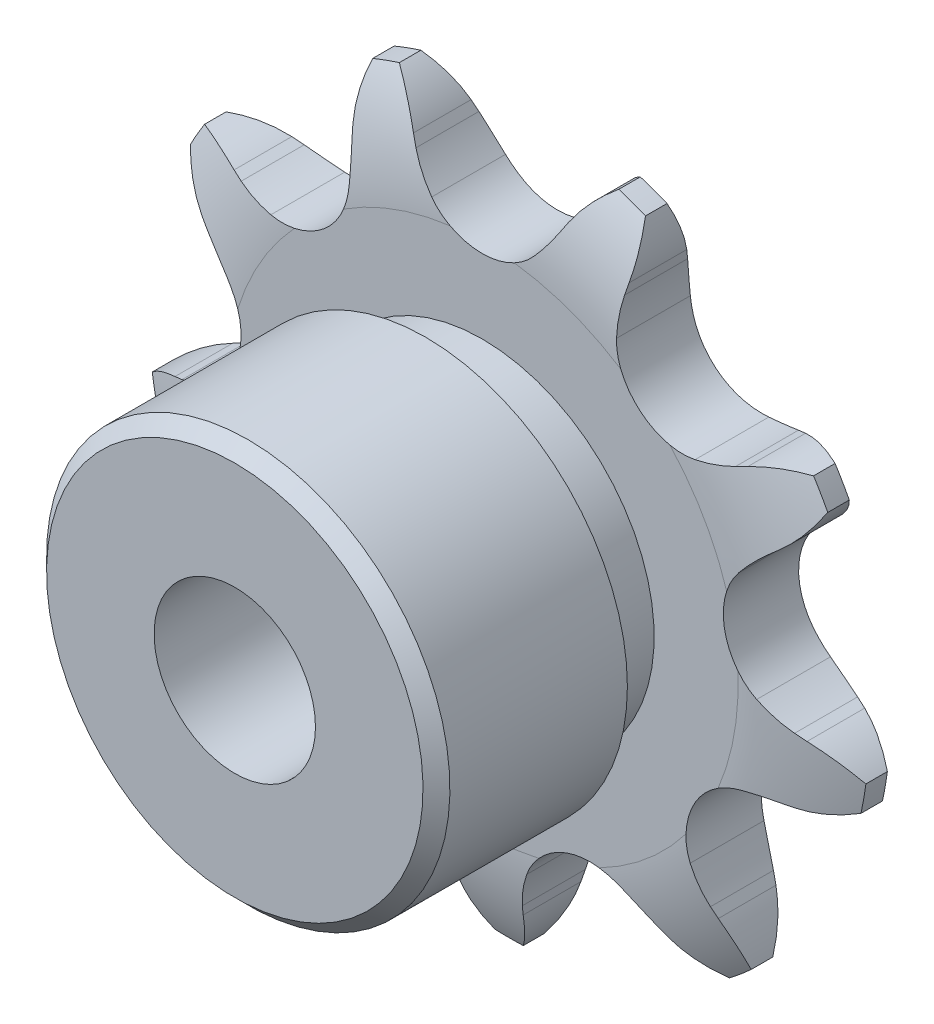
SolidWorks part; units mm, degrees
ref_plane "Front Plane" through (0, 0, 0) normal (0, 0, 1) x (1, 0, 0)
ref_plane "Top Plane" through (0, 0, 0) normal (0, 1, 0) x (1, 0, 0)
ref_plane "Right Plane" through (0, 0, 0) normal (1, 0, 0) x (0, 0, -1)
sketch "Sketch0" plane through (0, 0, 0) normal (0, 0, 1) x (1, 0, 0)
  line L0 (4, -10.9899) -> (0, 0) construction
  line L1 (0, 0) -> (10.1284, -5.8476) construction
  line L2 (0, 0) -> (-4, -10.9899) construction
  line L3 (4, -10.9899) -> (10.1284, -5.8476) construction
  line L4 (4, -10.9899) -> (-4, -10.9899) construction
  line L5 (6.6169, -9.7493) -> (6.322, -9.5008)
  line L6 (4, -10.9899) -> (0, -12.4458) construction
  line L7 (1.1979, -11.7217) -> (1.2641, -11.3417)
  line L8 (0, -10.9899) -> (0, -13.3899) construction
  line L9 (5.2105, -8.7449) -> (2.1016, -14.5107) construction
  line L10 (0, 0) -> (0, -10.9899) construction
  line L11 (6.322, -9.5008) -> (2.1016, -14.5107) construction
  line L12 (0, -13.3899) -> (0, -14.0161) construction
  line L13 (9.3623, -6.4904) -> (6.6169, -9.7493) construction
  circle A0 centre (0, 0) radius 13.3899 construction
  circle A1 centre (0, 0) radius 11.6952 construction
  arc A2 (-4.1222, -15.1007) -> (12.8643, -8.9181) centre (0, 0) ccw
  circle A3 centre (0, 0) radius 14.0161 construction
  circle A4 centre (4, -10.9899) radius 2.5 construction
  arc A7 (5.2105, -8.7449) -> (1.6296, -10.0482) centre (4, -10.9899) ccw
  circle A8 centre (4, -10.9899) radius 2.5506 construction
  arc A9 (6.6169, -9.7493) -> (12.8643, -8.9181) centre (9.3623, -6.4904) ccw
  arc A10 (6.322, -9.5008) -> (5.2105, -8.7449) centre (2.1016, -14.5107) ccw
  arc A11 (1.1979, -11.7217) -> (-4.1222, -15.1007) centre (-3, -10.9899) cw
  arc A12 (1.2641, -11.3417) -> (1.6296, -10.0482) centre (7.7174, -12.4667) cw
  dimension "D1" = 2.5506
  dimension "Dr" = 5
  dimension "Ds" = 5.1012
  dimension "R" = 2.5506
  dimension "Pitch" = 8
  dimension "A" = 41.667
  dimension "360/N" = 40
  dimension "B" = 11.778
  dimension "ab" = 7
  dimension "J" = 2.4
  dimension "ac" = 4
sketch "Sketch1" plane through (0, 0, 0) normal (1, 0, 0) x (0, 0, -1)
  line L0 (1.4, 0) -> (-1.4, 0)
  line L1 (-1.4, 0) -> (-1.4, 9.5169)
  line L2 (-1.4, 11.6952) -> (0, 11.6952) construction
  line L3 (-0.4, 13.3899) -> (0.4, 13.3899)
  line L5 (1.4, 9.5169) -> (1.4, 0)
  line L7 (0, 13.3899) -> (0, 0) construction
  line L8 (-1.4, 9.5169) -> (1.4, 9.5169) construction
  line L9 (0, 13.3899) -> (0, -13.3899) construction
  line L10 (-1.4, 9.5169) -> (-1.4, 13.3899) construction
  line L11 (-1.4, 13.3899) -> (-0.4, 13.3899) construction
  line L12 (0.4, 13.3899) -> (1.4, 13.3899) construction
  line L13 (1.4, 13.3899) -> (1.4, 9.5169) construction
  line L14 (0, 0) -> (-6.4008, 0) construction
  line L15 (-1.4, 11.6952) -> (-1.4, 6.3952) construction
  line L22 (1.4, 0) -> (-10.6, 0) construction
  line L24 (-1.4, 0) -> (-1.4, 6.3952) construction
  arc A0 (-0.4, 13.3899) -> (-1.4, 9.5169) centre (6.6, 9.5169) ccw
  arc A1 (0.4, 13.3899) -> (1.4, 9.5169) centre (-6.6, 9.5169) cw
  dimension "R" = 8
  dimension "t" = 2.8
  dimension "C" = 1
  dimension "A" = 3.873
  dimension "K" = 6.4008
  dimension "Width" = 12
  dimension "H" = 5.3
revolve "Revolve1" add sketch "Sketch1" angle 360 about L0
extrude "Cut-Extrude1" cut sketch "Sketch0" against normal through all and the other way through all
pattern_circular "CirPattern1" count 9 over 360 about axis through (0, 0, 0) along (0, 0, 1) of "Cut-Extrude1"
sketch "Sketch2" plane through (0, 0, 0) normal (0, 0, 1) x (1, 0, 0)
  circle A0 centre (0, 0) radius 3 construction
  circle A1 centre (0, 0) radius 7.5
  circle A2 centre (0, 0) radius 13.39 construction
  dimension "Bore" = 6
  dimension "Hub Dia." = 15
  dimension "OD" = 26.78
extrude "Boss-Extrude1" add sketch "Sketch2" along normal up to vertex (10.6 mm away) from surface at 1.4 starting at face at (0, 0, 1.4)
sketch "Sketch3" plane through (0, 0, 0) normal (0, 0, 1) x (1, 0, 0)
  circle A0 centre (0, 0) radius 3 construction
  circle A1 centre (0, 0) radius 3
extrude "Cut-Extrude2" cut sketch "Sketch3" along normal through all and the other way through all
sketch "Sketch4" plane through (0, 0, 0) normal (1, 0, 0) x (0, 0, -1)
  line L0 (-10.6, 7.5) -> (-10.6, 7)
  line L1 (-1.4, 13.3899) -> (-3.5, 13.3899)
  line L2 (-1.4, 13.3899) -> (-1.4, 6.3952)
  line L3 (-1.4, 6.3952) -> (-3.5, 6.3952)
  line L4 (-3.5, 13.3899) -> (-3.5, 6.3952)
  line L9 (-10.6, 7) -> (-10.1, 7.5)
  line L10 (-10.1, 7.5) -> (-10.6, 7.5)
  dimension "C" = 0.5
  dimension "D3" = 2.1
revolve "Cut-Revolve1" cut sketch "Sketch4" angle 360 about L22
sketch "Sketch5" plane through (0, 0, 0) normal (0, 0, 1) x (1, 0, 0)
  circle A0 centre (0, 0) radius 13.39 construction
  circle A1 centre (0, 0) radius 13.39
extrude "Cut-Extrude3" [suppressed] cut sketch "Sketch5" against normal through all and the other way through all flip side to cut
equation "\"360/N@Sketch0\" = 360/\"Teeth@CirPattern1\""
equation "\"Ds@Sketch0\" = 1.005 * \"Dr@Sketch0\" + ( 0.003 * 25.4 ) "
equation "\"R@Sketch0\" = 1/2 * \"Ds@Sketch0\""
equation "\"A@Sketch0\" = 35 +  ( 60 / \"Teeth@CirPattern1\" ) "
equation "\"B@Sketch0\" = 18 -  ( 56 / \"Teeth@CirPattern1\" )"
equation "\"ac@Sketch0\" = 0.8 * \"Dr@Sketch0\""
equation "\"ab@Sketch0\" = 1.4 * \"Dr@Sketch0\""
equation "\"J@Sketch0\" = 0.3 * \"Pitch@Sketch0\""
equation "\"D3@Sketch4\" = \"t@Sketch1\" * 3 / 4"
